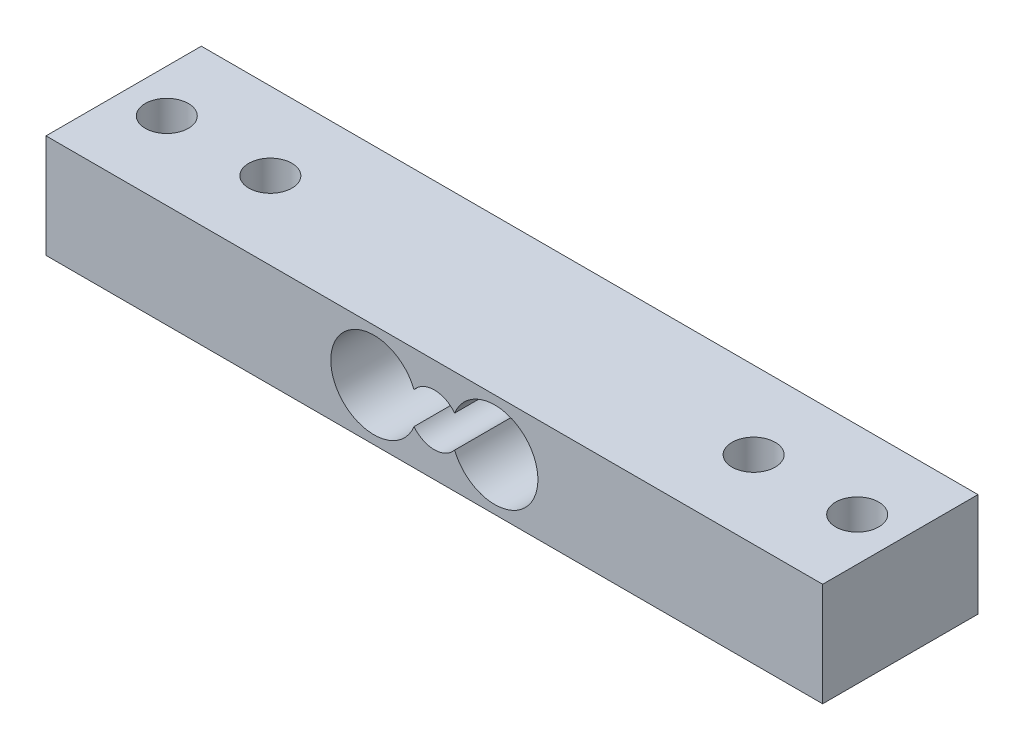
SolidWorks part; units mm, degrees
ref_plane "前视基准面" through (0, 0, 0) normal (0, 0, 1) x (1, 0, 0)
ref_plane "上视基准面" through (0, 0, 0) normal (0, 1, 0) x (1, 0, 0)
ref_plane "右视基准面" through (0, 0, 0) normal (1, 0, 0) x (0, 0, -1)
sketch "草图1" plane through (0, 0, 0) normal (0, 1, 0) x (1, 0, 0)
  line L1 (0, 0) -> (45, 0)
  line L2 (0, 0) -> (0, 9)
  line L3 (0, 9) -> (45, 9)
  line L4 (45, 0) -> (45, 9)
  dimension "D1" = 45
  dimension "D2" = 9
extrude "凸台-拉伸1" add sketch "草图1" along normal blind 6
hole_wizard "M3 螺纹孔1" positions "草图2" profile "草图3" tap size "M3" standard "GB" end condition through all
sketch "草图2" plane through (0, 6, 0) normal (0, 1, 0) x (1, 0, 0)
  line L0 (0, 4.5) -> (45, 4.5) construction
  line L1 (0, 9) -> (0, 0) construction
  line L2 (45, 0) -> (45, 9) construction
  line L3 (22.5, 9) -> (22.5, -1.9919) construction
  line L4 (45, 9) -> (0, 9) construction
  point P9 (2.5, 4.5)
  point P11 (8.5, 4.5)
  point P20 (36.5, 4.5)
  point P21 (42.5, 4.5)
  dimension "D1" = 40
  dimension "D2" = 28
sketch "草图3" plane through (2.5, 6, -4.5) normal (1, 0, 0) x (0, 0, 1)
  line L0 (0, 0) -> (0, 6)
  line L1 (0, 6) -> (1.25, 6)
  line L2 (1.25, 6) -> (1.25, 0)
  line L5 (1.25, 0) -> (0, 0)
  line L11 (0, -6.35) -> (0, 107.95) construction
  dimension "通孔螺纹孔钻头直径" = 2.5
  dimension "通孔螺纹孔钻头深度" = 6
cosmetic thread "孔螺蚊线1" parameters "D2"=3
cosmetic thread "孔螺蚊线2" parameters "D2"=3
cosmetic thread "孔螺蚊线3" parameters "D2"=3
cosmetic thread "孔螺蚊线4" parameters "D2"=3
sketch "草图4" plane through (0, 0, 0) normal (0, 0, 1) x (1, 0, 0)
  line L0 (0, 3) -> (45, 3) construction
  line L1 (0, 6) -> (0, 0) construction
  line L2 (45, 6) -> (45, 0) construction
  line L3 (22.5, 6) -> (22.5, 0) construction
  line L4 (0, 6) -> (45, 6) construction
  line L5 (0, 0) -> (45, 0) construction
  arc A0 (21.3214, 2.0721) -> (23.6786, 2.0721) centre (22.5, 3) ccw
  arc A1 (21.3214, 3.9279) -> (21.3214, 2.0721) centre (19, 3) ccw
  arc A2 (23.6786, 3.9279) -> (23.6786, 2.0721) centre (26, 3) cw
  arc A3 (23.6786, 3.9279) -> (21.3214, 3.9279) centre (22.5, 3) ccw
  dimension "D1" = 7
  dimension "D2" = 5
  dimension "D3" = 3
extrude "切除-拉伸1" cut sketch "草图4" against normal through all
